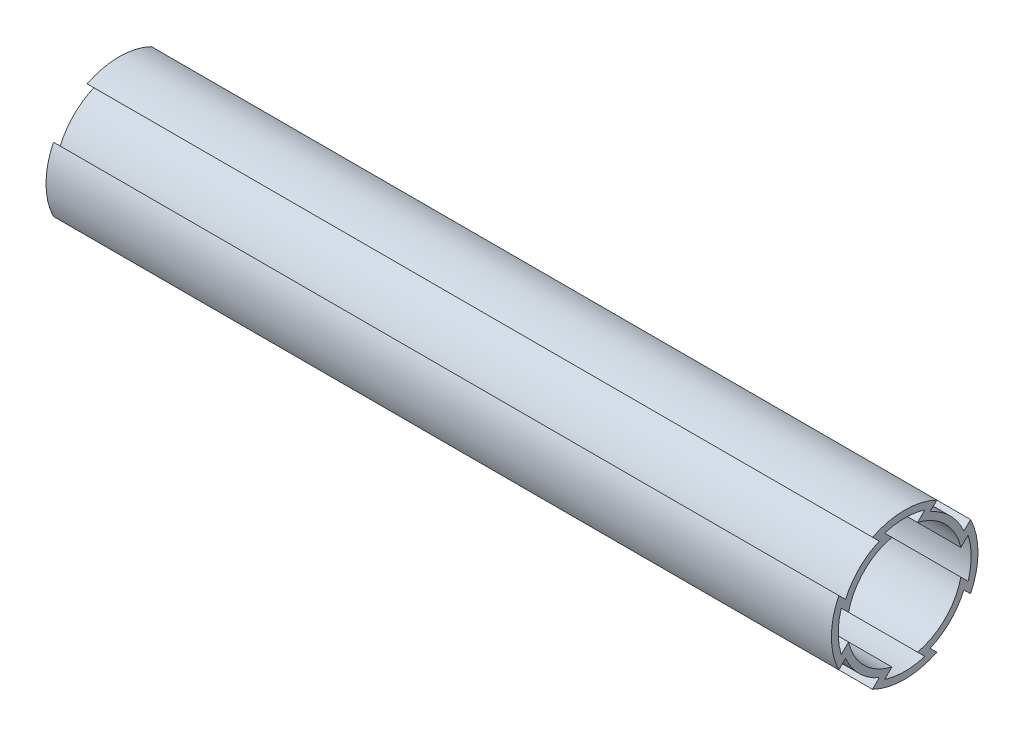
SolidWorks part; units mm, degrees
ref_plane "Front Plane" through (0, 0, 0) normal (0, 0, 1) x (1, 0, 0)
ref_plane "Top Plane" through (0, 0, 0) normal (0, 1, 0) x (1, 0, 0)
ref_plane "Right Plane" through (0, 0, 0) normal (1, 0, 0) x (0, 0, -1)
sketch "Sketch1" plane through (0, 0, 0) normal (1, 0, 0) x (0, 0, -1)
  line L16 (-11.2978, 4.8631) -> (-12.5794, 6.1448)
  line L17 (-12.5794, -6.1448) -> (-11.2978, -4.8631)
  line L18 (-4.8631, -11.2978) -> (-6.1448, -12.5794)
  line L19 (6.1448, -12.5794) -> (4.8631, -11.2978)
  line L20 (11.2978, -4.8631) -> (12.5794, -6.1448)
  line L21 (12.5794, 6.1448) -> (11.2978, 4.8631)
  line L22 (4.8631, 11.2978) -> (6.1448, 12.5794)
  line L23 (-6.1448, 12.5794) -> (-4.8631, 11.2978)
  line L24 (-10.7236, 2.4504) -> (-12.1074, 3.8342)
  line L25 (-12.1074, -3.8342) -> (-10.7236, -2.4504)
  line L26 (-2.4504, -10.7236) -> (-3.8342, -12.1074)
  line L27 (3.8342, -12.1074) -> (2.4504, -10.7236)
  line L28 (10.7236, -2.4504) -> (12.1074, -3.8342)
  line L29 (12.1074, 3.8342) -> (10.7236, 2.4504)
  line L30 (2.4504, 10.7236) -> (3.8342, 12.1074)
  line L31 (-3.8342, 12.1074) -> (-2.4504, 10.7236)
  arc A18 (-12.5794, 6.1448) -> (-12.5794, -6.1448) centre (0, 0) ccw
  arc A19 (-11.2978, -4.8631) -> (-4.8631, -11.2978) centre (0, 0) ccw
  arc A20 (-6.1448, -12.5794) -> (6.1448, -12.5794) centre (0, 0) ccw
  arc A21 (4.8631, -11.2978) -> (11.2978, -4.8631) centre (0, 0) ccw
  arc A22 (12.5794, -6.1448) -> (14, 0) centre (0, 0) ccw
  arc A23 (14, 0) -> (12.5794, 6.1448) centre (0, 0) ccw
  arc A24 (11.2978, 4.8631) -> (4.8631, 11.2978) centre (0, 0) ccw
  arc A25 (6.1448, 12.5794) -> (-6.1448, 12.5794) centre (0, 0) ccw
  arc A26 (-4.8631, 11.2978) -> (-11.2978, 4.8631) centre (0, 0) ccw
  arc A27 (-12.1074, 3.8342) -> (-12.1074, -3.8342) centre (0, 0) ccw
  arc A28 (-10.7236, -2.4504) -> (-2.4504, -10.7236) centre (0, 0) ccw
  arc A29 (-3.8342, -12.1074) -> (3.8342, -12.1074) centre (0, 0) ccw
  arc A30 (2.4504, -10.7236) -> (10.7236, -2.4504) centre (0, 0) ccw
  arc A31 (12.1074, -3.8342) -> (12.7, 0) centre (0, 0) ccw
  arc A32 (12.7, 0) -> (12.1074, 3.8342) centre (0, 0) ccw
  arc A33 (10.7236, 2.4504) -> (2.4504, 10.7236) centre (0, 0) ccw
  arc A34 (3.8342, 12.1074) -> (-3.8342, 12.1074) centre (0, 0) ccw
  arc A35 (-2.4504, 10.7236) -> (-10.7236, 2.4504) centre (0, 0) ccw
  dimension "D1" = 1.3
extrude "Boss-Extrude1" add sketch "Sketch1" along normal blind 150
